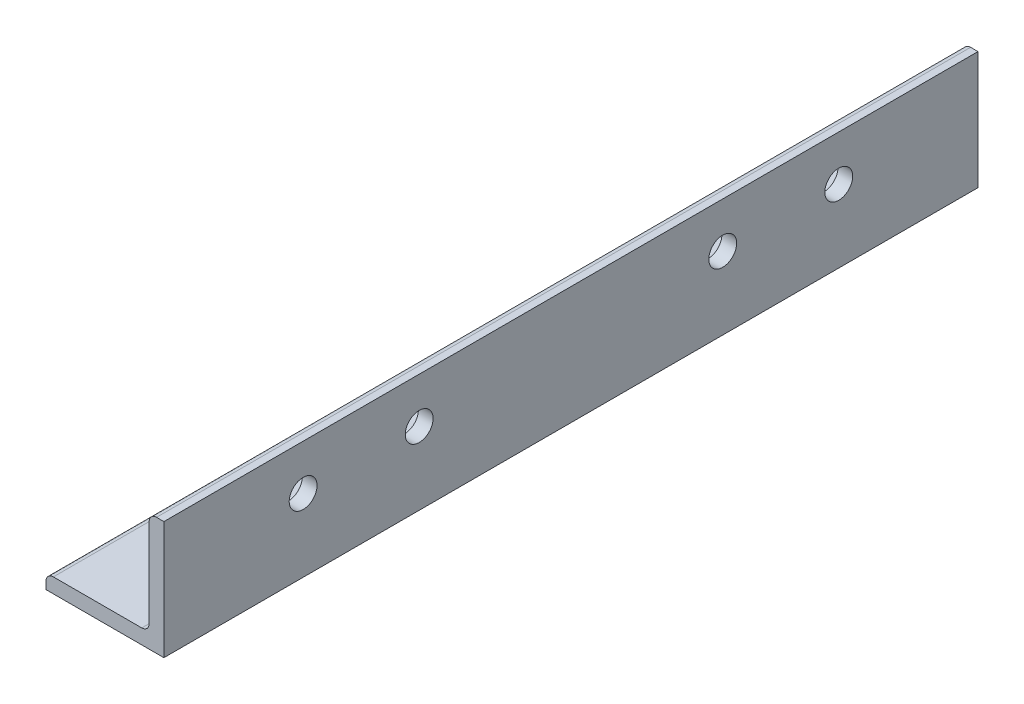
SolidWorks part; units mm, degrees
material "6061 Alloy"
ref_plane "Front Plane" through (0, 0, 0) normal (0, 0, 1) x (1, 0, 0)
ref_plane "Top Plane" through (0, 0, 0) normal (0, 1, 0) x (1, 0, 0)
ref_plane "Right Plane" through (0, 0, 0) normal (1, 0, 0) x (0, 0, -1)
sketch "Sketch2" plane through (0, 0, 0) normal (0, 0, 1) x (1, 0, 0)
  line L0 (-12.7, 0) -> (12.7, 0)
  line L1 (12.7, 0) -> (12.7, 25.4)
  line L2 (12.7, 25.4) -> (9.525, 25.4) construction
  line L3 (9.525, 23.8125) -> (9.525, 4.7625)
  line L4 (7.9375, 3.175) -> (-11.1125, 3.175)
  line L5 (-12.7, 0) -> (-12.7, 3.175) construction
  line L6 (11.1125, 25.4) -> (12.7, 25.4)
  line L7 (-12.7, 1.5875) -> (-12.7, 0)
  arc A0 (9.525, 23.8125) -> (11.1125, 25.4) centre (11.1125, 23.8125) cw
  arc A1 (-12.7, 1.5875) -> (-11.1125, 3.175) centre (-11.1125, 1.5875) cw
  arc A2 (9.525, 4.7625) -> (7.9375, 3.175) centre (7.9375, 4.7625) cw
  dimension "Vert" = 25.4
  dimension "Horz" = 25.4
  dimension "Thickness" = 3.175
extrude "Boss-Extrude1" add sketch "Sketch2" along normal mid plane 175.3969
sketch "Sketch3" plane through (0, 0, 0) normal (0, -1, 0) x (1, 0, 0)
  line L0 (0, -103.9976) -> (0, 99.5165) construction
  line L1 (-12.7, -87.6985) -> (12.7, -87.6985) construction
  line L2 (-26.9494, 0) -> (36.898, 0) construction
  circle A0 centre (0, -37.6985) radius 3.175
  circle A1 centre (0, 37.6985) radius 3.175
  dimension "D1" = 50
extrude "Cut-Extrude1" cut sketch "Sketch3" against normal through all contours A0 | A1
sketch "Sketch4" plane through (9.525, 0, 0) normal (-1, 0, 0) x (0, 0, 1)
  line L0 (-20.9277, 15.6477) -> (-154.4692, 15.6477) construction
  line L4 (-87.6985, 23.8125) -> (-87.6985, 4.7625) construction
  line L6 (0, -13.97) -> (0, 13.97) construction
  line L7 (87.6985, 23.8125) -> (87.6985, 4.7625) construction
  circle A1 centre (-57.6985, 15.6477) radius 3
  circle A2 centre (-32.6985, 15.6477) radius 3
  circle A3 centre (57.6985, 15.6477) radius 3
  circle A4 centre (32.6985, 15.6477) radius 3
  point P6 (-66.3533, 15.6477)
  point P9 (-87.6985, 15.6477)
  point P10 (-100.6715, 15.6477)
  point P11 (-20.9277, 15.6477)
  point P12 (0, 0)
  point P13 (0, 0)
  point P14 (-87.6985, 14.2875)
  point P15 (0, 0)
  point P16 (-41.8067, 21.1836)
  point P17 (-38.4329, 16.2032)
  point P18 (-38.5936, 16.2836)
  dimension "D1" = 55
  dimension "D3" = 30
  dimension "D4" = 55
  dimension "D2" = 30
extrude "Cut-Extrude2" cut sketch "Sketch4" against normal through all
